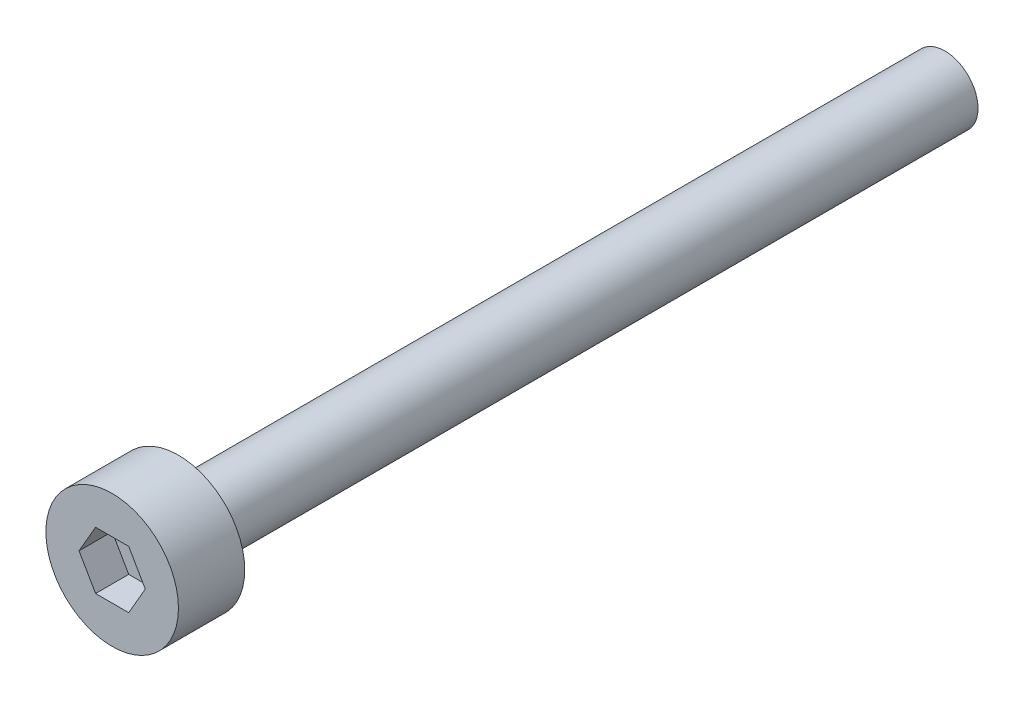
SolidWorks part; units mm, degrees
ref_plane "前视基准面" through (0, 0, 0) normal (0, 0, 1) x (1, 0, 0)
ref_plane "上视基准面" through (0, 0, 0) normal (0, 1, 0) x (1, 0, 0)
ref_plane "右视基准面" through (0, 0, 0) normal (1, 0, 0) x (0, 0, -1)
sketch "草图1" plane through (0, 0, 0) normal (0, 0, 1) x (1, 0, 0)
  circle A0 centre (0, 0) radius 1.6
extrude "凸台-拉伸1" add sketch "草图1" along normal blind 1.6
sketch "草图3" plane through (0, 0, 0) normal (0, 0, 1) x (1, 0, 0)
  circle A0 centre (0, 0) radius 0.8
extrude "凸台-拉伸2" add sketch "草图3" against normal blind 18.5 contours A0
sketch "草图4" plane through (0, 0, 1.6) normal (0, 0, 1) x (1, 0, 0)
  line L1 (0.8, 0) -> (0.4, 0.6928)
  line L2 (0.4, 0.6928) -> (-0.4, 0.6928)
  line L3 (-0.4, 0.6928) -> (-0.8, 0)
  line L4 (-0.8, 0) -> (-0.4, -0.6928)
  line L5 (-0.4, -0.6928) -> (0.4, -0.6928)
  line L6 (0.4, -0.6928) -> (0.8, 0)
  circle A0 centre (0, 0) radius 0.8 construction
extrude "切除-拉伸1" cut sketch "草图4" against normal blind 0.8
